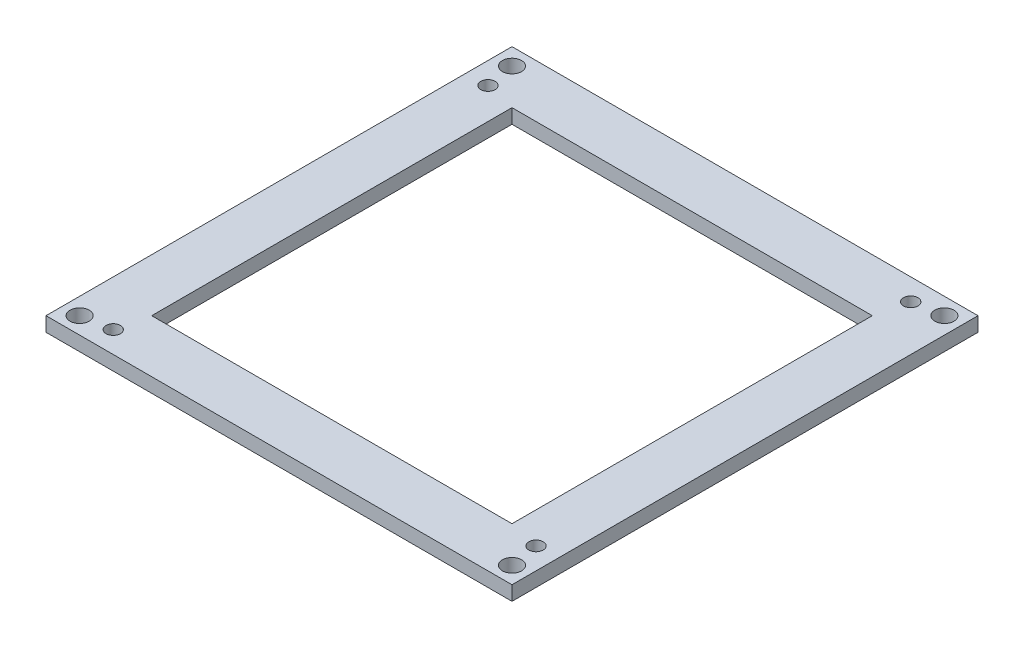
SolidWorks part; units mm, degrees
ref_plane "Front" through (0, 0, 0) normal (0, 0, 1) x (1, 0, 0)
ref_plane "Top" through (0, 0, 0) normal (0, 1, 0) x (1, 0, 0)
ref_plane "Right" through (0, 0, 0) normal (1, 0, 0) x (0, 0, -1)
sketch "Sketch1" plane through (0, 0, 0) normal (0, 1, 0) x (1, 0, 0)
  line L1 (0, 0) -> (97, 0)
  line L2 (0, 0) -> (0, 97)
  line L3 (0, 97) -> (97, 97)
  line L4 (97, 0) -> (97, 97)
  dimension "D1" = 97
  dimension "D2" = 97
extrude "Boss-Extrude1" add sketch "Sketch1" along normal blind 3
sketch "Sketch2" plane through (0, 3, 0) normal (0, 1, 0) x (1, 0, 0)
  line L0 (-1.5, -1.5) -> (98.5, -1.5)
  line L1 (-1.5, -1.5) -> (-1.5, 98.5)
  line L2 (-1.5, 98.5) -> (98.5, 98.5)
  line L3 (98.5, -1.5) -> (98.5, 98.5)
  line L4 (-1.5, -1.5) -> (98.5, 98.5) construction
  line L5 (-1.5, 98.5) -> (98.5, -1.5) construction
  line L6 (97, 97) -> (0, 97) construction
  line L7 (97, 0) -> (97, 97) construction
  line L10 (-1.5, 98.5) -> (7, 98.5)
  line L11 (-1.5, 98.5) -> (-1.5, 90)
  line L12 (-1.5, 90) -> (7, 90)
  line L13 (7, 98.5) -> (7, 90)
  line L14 (-1.5, -1.5) -> (7, -1.5)
  line L15 (-1.5, -1.5) -> (-1.5, 7)
  line L16 (-1.5, 7) -> (7, 7)
  line L17 (7, -1.5) -> (7, 7)
  line L18 (98.5, -1.5) -> (90, -1.5)
  line L19 (98.5, -1.5) -> (98.5, 7)
  line L20 (98.5, 7) -> (90, 7)
  line L21 (90, -1.5) -> (90, 7)
  line L22 (98.5, 98.5) -> (90, 98.5)
  line L23 (98.5, 98.5) -> (98.5, 90)
  line L24 (98.5, 90) -> (90, 90)
  line L25 (90, 98.5) -> (90, 90)
  circle A0 centre (4.5, 87.5) radius 1.5
  circle A1 centre (87.5, 92.5) radius 1.5
  circle A2 centre (92.5, 9.5) radius 1.5
  circle A3 centre (9.5, 4.5) radius 1.5
  point P0 (48.5454, 89.2736)
  point P1 (48.5454, 6.2736)
  point P2 (90.0454, 47.7736)
  point P3 (48.5, 48.5)
  point P16 (48.5, 97)
  point P17 (97, 48.5)
  dimension "D1" = 6
  dimension "D2" = 11
  dimension "D3" = 6
  dimension "D4" = 8.5
  dimension "D5" = 100
  dimension "D6" = 8.5
  dimension "D7" = 8.5
  dimension "D8" = 2.5
  dimension "D9" = 2.5
  dimension "D10" = 2.5
  dimension "D11" = 2.5
  dimension "D12" = 2.5
extrude "Cut-Extrude4" cut sketch "Sketch2" against normal through all contours A0 | A1 | A3 | A2
sketch "Sketch3" plane through (0, 3, 0) normal (0, 1, 0) x (1, 0, 0)
  line L0 (97, 97) -> (0, 97) construction
  line L1 (97, 0) -> (97, 97) construction
  line L3 (11, 11) -> (86, 11)
  line L4 (11, 11) -> (11, 86)
  line L5 (11, 86) -> (86, 86)
  line L6 (86, 11) -> (86, 86)
  line L7 (11, 11) -> (86, 86) construction
  line L8 (11, 86) -> (86, 11) construction
  point P0 (48.5, 97)
  point P1 (97, 48.5)
  point P4 (48.5, 48.5)
  dimension "D1" = 75
  dimension "D2" = 75
extrude "Cut-Extrude5" cut sketch "Sketch3" against normal blind 7
sketch "Sketch4" plane through (0, 3, 0) normal (0, 1, 0) x (1, 0, 0)
  line L1 (97, 0) -> (86, 0)
  line L2 (97, 0) -> (97, 11)
  line L3 (97, 11) -> (86, 11)
  line L4 (86, 0) -> (86, 11)
  line L5 (0, 97) -> (11, 97)
  line L6 (0, 97) -> (0, 86)
  line L7 (0, 86) -> (11, 86)
  line L8 (11, 97) -> (11, 86)
  circle A0 centre (93.5, 3.5) radius 2
  circle A1 centre (3.5, 93.5) radius 2
  circle A2 centre (93.5, 93.5) radius 2
  circle A3 centre (3.5, 3.5) radius 2
  point P12 (91.5, 0)
  point P13 (86, 5.5)
  point P14 (5.5, 86)
  point P15 (11, 91.5)
  dimension "D1" = 4
  dimension "D2" = 4
extrude "Cut-Extrude6" cut sketch "Sketch4" against normal blind 10 contours A0 | A2 | A1 | A3
